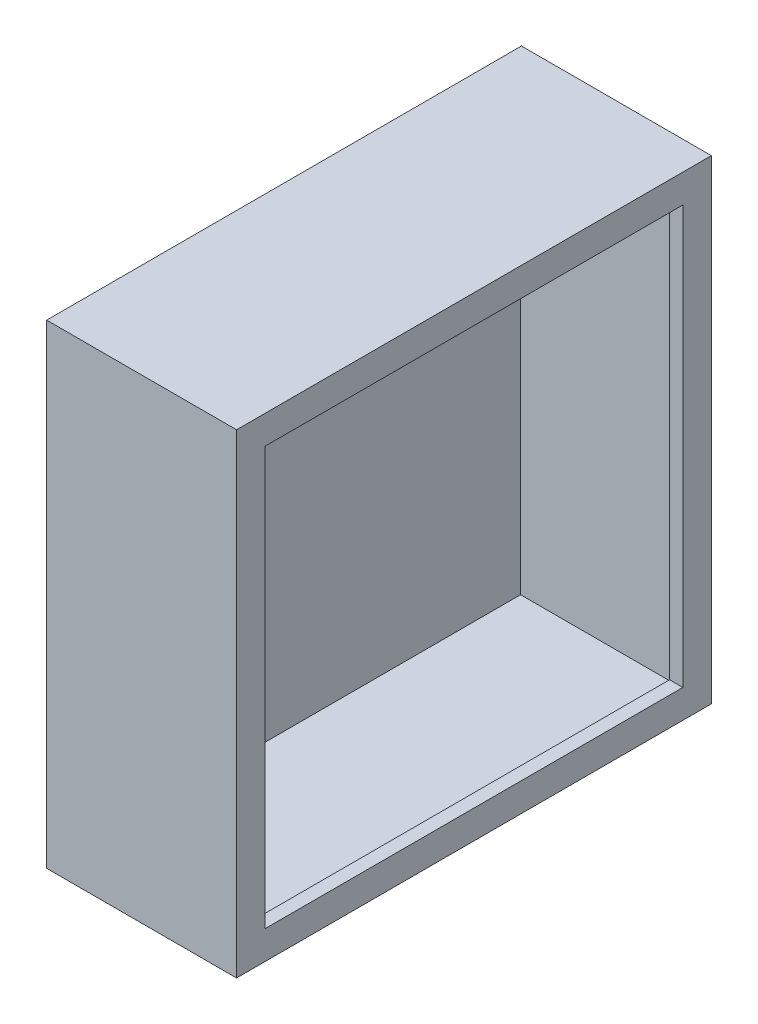
SolidWorks part; units mm, degrees
ref_plane "前视基准面" through (0, 0, 0) normal (0, 0, 1) x (1, 0, 0)
ref_plane "上视基准面" through (0, 0, 0) normal (0, 1, 0) x (1, 0, 0)
ref_plane "右视基准面" through (0, 0, 0) normal (1, 0, 0) x (0, 0, -1)
other "Configuration Table"
sketch "草图1" plane through (0, 0, 0) normal (1, 0, 0) x (0, 0, -1)
  line L1 (-43.6548, 60.1782) -> (56.3452, 60.1782)
  line L2 (-43.6548, 60.1782) -> (-43.6548, -39.8218)
  line L3 (-43.6548, -39.8218) -> (56.3452, -39.8218)
  line L4 (56.3452, 60.1782) -> (56.3452, -39.8218)
  dimension "D1" = 100
  dimension "D2" = 100
extrude "凸台-拉伸1" add sketch "草图1" along normal blind 40
sketch "草图2" plane through (40, 0, 0) normal (1, 0, 0) x (0, 0, -1)
  line L0 (-37.6548, 54.1782) -> (-37.6548, -33.8218) construction
  line L5 (50.3452, 54.1782) -> (50.3452, -33.8218)
  line L10 (-37.6548, -33.8218) -> (50.3452, -33.8218) construction
  line L13 (-37.6548, 54.1782) -> (50.3452, 54.1782) construction
  point P8 (0, 0)
sketch "草图4" plane through (0, 0, 43.6548) normal (0, 0, 1) x (1, 0, 0)
  line L0 (40, 54.1782) -> (37, 54.1782)
  line L1 (40, 54.1782) -> (40, -33.8218) construction
  line L2 (40, 54.1782) -> (40, -33.8218)
  line L3 (40, -33.8218) -> (37, -33.8218)
  line L4 (3, 57.1782) -> (37, 57.1782)
  line L5 (37, -33.8218) -> (37, 57.1782)
  line L6 (37, 57.1782) -> (37, -36.8218)
  line L9 (3, -36.8218) -> (37, -36.8218)
  line L10 (3, 57.1782) -> (3, -36.8218)
  line M11 (40, -39.8218) -> (40, 60.1782)
sketch "草图6" plane through (0, 60.1782, 0) normal (0, 1, 0) x (1, 0, 0)
  line L0 (0, 56.3452) -> (3, 56.3452)
  line L1 (40, 56.3452) -> (0, 56.3452) construction
  line L2 (3.2049, 53.1638) -> (37.2049, 53.1638)
  line L3 (37.2049, 53.1638) -> (37.2049, -40.8362)
  line L4 (3.2049, -40.8362) -> (37.2049, -40.8362)
  line L5 (3.2049, 53.1638) -> (3.2049, -40.8362)
  line L6 (0, 56.3452) -> (0, 53.3452)
  line L7 (0, 56.3452) -> (0, -43.6548) construction
  dimension "D1" = 3
  dimension "D2" = 3
sketch "草图8" plane through (0, 0, -56.3452) normal (0, 0, -1) x (-1, 0, 0)
  line L0 (-37.2049, 57.1782) -> (-3.2049, 57.1782)
  line L1 (-3.2049, 57.1782) -> (-3.2049, -36.8218)
  line L2 (-37.2049, -36.8218) -> (-3.2049, -36.8218)
  line L3 (-37.2049, 57.1782) -> (-37.2049, -36.8218)
  line L9 (-3, -36.8218) -> (-37, -36.8218) construction
  point P4 (0, 0)
  point P5 (0, 0)
sketch "草图10" plane through (0, -39.8218, 0) normal (0, -1, 0) x (1, 0, 0)
  line L1 (3.2049, 40.8362) -> (37.2049, 40.8362)
  line L2 (3.2049, 40.8362) -> (3.2049, -53.1638)
  line L3 (3.2049, -53.1638) -> (37.2049, -53.1638)
  line L4 (37.2049, 40.8362) -> (37.2049, -53.1638)
  point P6 (0, 0)
sketch "草图12" plane through (0, 0, 0) normal (-1, 0, 0) x (0, 0, 1)
  line L0 (40.8362, 60.1782) -> (43.6548, 57.1782)
  line L1 (-53.1638, 60.1782) -> (40.8362, 60.1782) construction
  line L2 (-53.1638, 60.1782) -> (40.8362, 60.1782) construction
  line L3 (43.6548, 57.1782) -> (43.6548, -36.8218) construction
  line L4 (43.6548, 57.1782) -> (43.6548, -36.8218) construction
  line L5 (-56.3452, -36.8218) -> (-53.1638, -39.8218)
  line L6 (-56.3452, 57.1782) -> (-56.3452, -36.8218) construction
  line L7 (-56.3452, 57.1782) -> (-56.3452, -36.8218) construction
  line L8 (40.8362, -39.8218) -> (-53.1638, -39.8218) construction
  line L9 (43.6548, -36.8218) -> (40.8362, -39.8218)
  line L10 (43.6548, -39.8218) -> (-56.3452, -39.8218) construction
  point P22 (0, 0)
  point P23 (0, 0)
  point P25 (0, 0)
  point P26 (0, 0)
  point P27 (0, 0)
  point P28 (0, 0)
sketch "草图13" plane through (0, 0, 43.6548) normal (0, 0, 1) x (1, 0, 0)
  line L0 (0, -36.8218) -> (3, -36.8218)
  line L1 (0, -36.8218) -> (0, -39.8218) construction
  point P5 (0, -36.8218)
sketch "草图14" plane through (0, -39.8218, 0) normal (0, -1, 0) x (1, 0, 0)
  line L0 (0, 40.8362) -> (3.2049, 40.8362)
  line L1 (0, 40.8362) -> (0, 43.6548) construction
sketch "草图18" plane through (40, 0, 0) normal (1, 0, 0) x (0, 0, -1)
  line L0 (-43.6548, -36.8218) -> (-40.8362, -39.8218)
  line L1 (-43.6548, -36.8218) -> (-43.6548, -39.8218)
  line L2 (-43.6548, -39.8218) -> (-40.8362, -39.8218)
  point P4 (0, 0)
sketch "草图21" plane through (40, 0, 0) normal (1, 0, 0) x (0, 0, -1)
  line L0 (-43.6548, -36.8218) -> (-43.6548, -39.8218)
  line L1 (-43.6548, -39.8218) -> (-40.8362, -39.8218)
sketch "草图27" plane through (0, 0, 0) normal (-1, 0, 0) x (0, 0, 1)
  line L0 (43.6548, -36.8218) -> (43.6548, -39.8218)
  line L1 (43.6548, -39.8218) -> (40.8362, -39.8218)
sketch "草图33" plane through (0, 0, 0) normal (-1, 0, 0) x (0, 0, 1)
  line L0 (43.6548, -36.8218) -> (43.6548, -39.8218)
  line L1 (43.6548, -39.8218) -> (40.8362, -39.8218)
  line L2 (43.6548, -36.8218) -> (40.8362, -39.8218)
sketch "草图36" plane through (40, 0, 0) normal (1, 0, 0) x (0, 0, -1)
  line L0 (-40.8362, 57.1782) -> (-40.8362, -36.8218)
  line L1 (53.1638, 57.1782) -> (-40.8362, 57.1782)
  line L2 (-40.8362, -36.8218) -> (53.1638, -36.8218)
  line L3 (53.1638, -36.8218) -> (53.1638, 57.1782)
  line L4 (-40.8362, 57.1782) -> (53.1638, 57.1782) construction
  line L5 (53.1638, 57.1782) -> (53.1638, -36.8218) construction
  line L6 (-40.8362, -36.8218) -> (53.1638, -36.8218) construction
  line L7 (-40.8362, 57.1782) -> (-40.8362, -36.8218) construction
sketch "草图39" plane through (40, 0, 0) normal (1, 0, 0) x (0, 0, -1)
extrude "切除-拉伸2" cut sketch "草图36" against normal blind 37 contours L0 L2 L3 L1
extrude "凸台-拉伸6" add sketch "草图4" against normal blind 6 contours L5 L3 L0 M11
sketch "草图52" plane through (0, 0, -56.3452) normal (0, 0, -1) x (-1, 0, 0)
  line L0 (-40, 54.1782) -> (-37.2049, 54.1782)
  line L1 (-37.2049, 57.1782) -> (-37.2049, -36.8218) construction
  line L2 (-40, 54.1782) -> (-40, -33.8218)
  line L3 (-40, 54.1782) -> (-40, -33.8218) construction
  line L4 (-40, -33.8218) -> (-37.2049, -33.8218)
  line L5 (-37.2049, -33.8218) -> (-37.2049, 54.1782)
extrude "凸台-拉伸7" add sketch "草图52" against normal blind 6 contours L5 L0 L2 L4
sketch "草图56" plane through (0, -39.8218, 0) normal (0, -1, 0) x (1, 0, 0)
  line L0 (37.2049, 40.8362) -> (40, 40.8362)
  line L1 (40, 40.8362) -> (40, -50.3452)
  line L2 (37.2049, 40.8362) -> (37.2049, -53.1638)
  line L3 (37.2049, -53.1638) -> (40, -53.1638)
  line L4 (40, -53.1638) -> (40, 40.8362)
  line M3 (40, -56.3452) -> (40, 43.6548)
extrude "凸台-拉伸9" add sketch "草图56" against normal blind 6 contours L2 L3 L0 M3
sketch "草图57" plane through (0, 60.1782, 0) normal (0, 1, 0) x (1, 0, 0)
  line L0 (37.2049, 53.1638) -> (37.2049, -40.8362)
  line L1 (37.2049, -40.8362) -> (40, -40.8362)
  line L2 (40, -43.6548) -> (40, -40.8362) construction
  line L3 (40, 56.3452) -> (40, -43.6548) construction
  line L4 (40, -40.8362) -> (40, 53.1638)
  line L5 (40, 53.1638) -> (37.2049, 53.1638)
extrude "凸台-拉伸10" add sketch "草图57" against normal blind 6 contours L5 L0 L1 L4
sketch "草图61" plane through (0, 0, 0) normal (-1, 0, 0) x (0, 0, 1)
